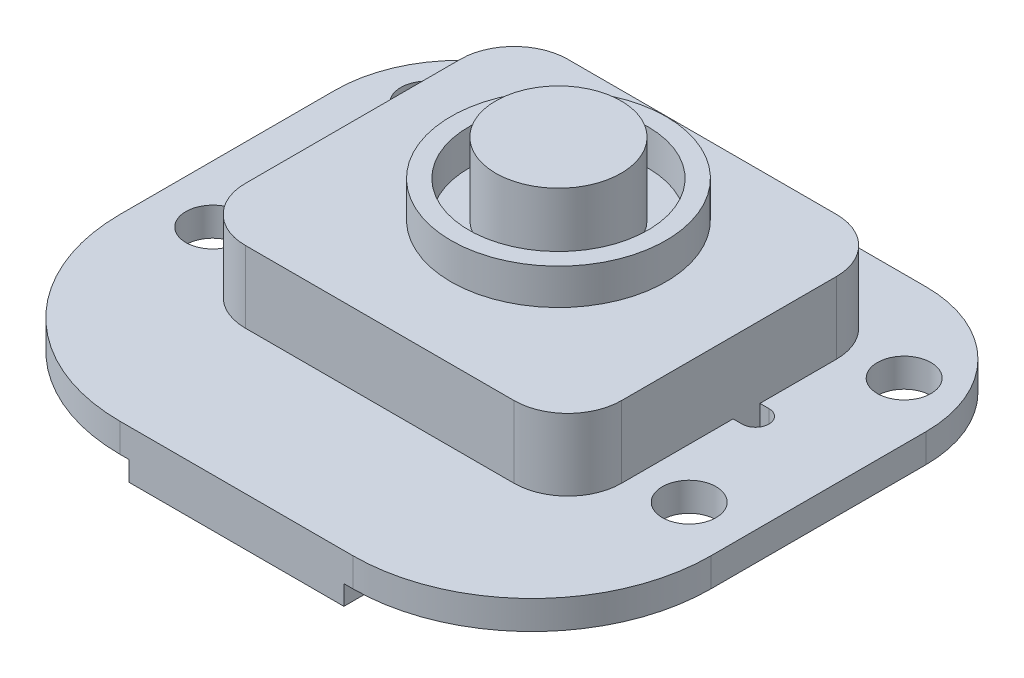
SolidWorks part; units mm, degrees
material "电源线路板"
ref_plane "前视基准面" through (0, 0, 0) normal (0, 0, 1) x (1, 0, 0)
ref_plane "上视基准面" through (0, 0, 0) normal (0, 1, 0) x (1, 0, 0)
ref_plane "右视基准面" through (0, 0, 0) normal (1, 0, 0) x (0, 0, -1)
other "Configuration Table"
sketch "草图1" plane through (0, 0, 0) normal (0, 1, 0) x (1, 0, 0)
  line L0 (0, 0) -> (0, -4.2094)
  line L1 (0, 0) -> (3.6442, 0)
  line L2 (-11, 0) -> (-10, 0) construction
  line L3 (-11, 0.75) -> (-10, 0.75)
  line L4 (-11, -0.75) -> (-10, -0.75)
  line L5 (11, 0) -> (10, 0) construction
  line L6 (11, 0.75) -> (10, 0.75)
  line L7 (-9.5, 11.0225) -> (9.5, 11.0225)
  line L8 (-16.5, 4.0225) -> (-16.5, -7.9775)
  line L9 (-6.5, -17.9775) -> (6.5, -17.9775)
  line L10 (16.5, 4.0225) -> (16.5, -7.9775)
  line L11 (11, -0.75) -> (10, -0.75)
  arc A0 (-16.5, 4.0225) -> (-9.5, 11.0225) centre (-9.5, 4.0225) cw
  arc A1 (16.5, 4.0225) -> (9.5, 11.0225) centre (9.5, 4.0225) ccw
  arc A2 (-6.5, -17.9775) -> (-16.5, -7.9775) centre (-6.5, -7.9775) cw
  arc A3 (16.5, -7.9775) -> (6.5, -17.9775) centre (6.5, -7.9775) cw
  circle A4 centre (-13.3, 6) radius 1.5
  circle A5 centre (13.3, 6) radius 1.5
  circle A6 centre (-13.3, -6) radius 1.5
  circle A7 centre (13.3, -6) radius 1.5
  arc A8 (-11, 0.75) -> (-11, -0.75) centre (-11, 0) ccw
  arc A9 (-10, -0.75) -> (-10, 0.75) centre (-10, 0) ccw
  arc A10 (11, 0.75) -> (11, -0.75) centre (11, 0) cw
  arc A11 (10, -0.75) -> (10, 0.75) centre (10, 0) cw
  point P27 (-10.5, 0)
  point P34 (10.5, 0)
  dimension "D12" = 7
  dimension "D13" = 7
  dimension "D14" = 10
  dimension "D15" = 10
  dimension "D2" = 13.3
  dimension "D10" = 1
  dimension "D3" = 13.3
  dimension "D4" = 12
  dimension "D5" = 6
  dimension "D6" = 6
  dimension "D7" = 12
  dimension "D8" = 0
  dimension "D9" = 0
  dimension "D11" = 10.5
extrude "凸台-拉伸1" add sketch "草图1" along normal blind 1.6
sketch "草图2" plane through (0, 0, 0) normal (0, 1, 0) x (1, 0, 0)
  line L0 (0, 0) -> (0, -3.1954)
  line L1 (-7.5, 8.0225) -> (7.5, 8.0225)
  line L2 (-10.5, 5.0225) -> (-10.5, -6.9775)
  line L3 (-7.5, -9.9775) -> (7.5, -9.9775)
  line L4 (10.5, 5.0225) -> (10.5, -6.9775)
  line L5 (-9.5, 11.0225) -> (9.5, 11.0225) construction
  line L6 (-6.5, -17.9775) -> (6.5, -17.9775) construction
  arc A0 (-10.5, 5.0225) -> (-7.5, 8.0225) centre (-7.5, 5.0225) cw
  arc A1 (10.5, 5.0225) -> (7.5, 8.0225) centre (7.5, 5.0225) ccw
  arc A2 (7.5, -9.9775) -> (10.5, -6.9775) centre (7.5, -6.9775) ccw
  arc A3 (-7.5, -9.9775) -> (-10.5, -6.9775) centre (-7.5, -6.9775) cw
  dimension "D5" = 3
  dimension "D6" = 3
  dimension "D7" = 3
  dimension "D8" = 3
  dimension "D1" = 10.5
  dimension "D2" = 10.5
  dimension "D3" = 3
  dimension "D4" = 8
extrude "凸台-拉伸2" add sketch "草图2" along normal blind 5.6
sketch "草图3" plane through (0, 0, 0) normal (0, 1, 0) x (1, 0, 0)
  circle A0 centre (0, 0) radius 6
  circle A1 centre (0, 0) radius 5
extrude "凸台-拉伸3" add sketch "草图3" along normal blind 7.6
sketch "草图4" plane through (0, 0, 0) normal (0, 1, 0) x (1, 0, 0)
  circle A0 centre (0, 0) radius 2.75
  circle A1 centre (0, 0) radius 3.5
  dimension "D1" = 5.5
extrude "凸台-拉伸4" add sketch "草图4" along normal blind 9.6
sketch "草图5" plane through (0, 0, 0) normal (0, 1, 0) x (1, 0, 0)
  circle A0 centre (0, 0) radius 3.5
extrude "凸台-拉伸5" add sketch "草图5" along normal blind 9.6
sketch "草图7" plane through (0, 0, 0) normal (0, 1, 0) x (1, 0, 0)
  line L0 (-6.5, -17.9775) -> (6.5, -17.9775) construction
  line L1 (6, -13.2607) -> (-6, -13.2607)
  line L2 (6, -13.2607) -> (6, -17.9775)
  line L3 (6, -17.9775) -> (-6, -17.9775)
  line L4 (-6, -13.2607) -> (-6, -17.9775)
  line L5 (0, 0) -> (0, -3.2289)
  dimension "D1" = 6
  dimension "D2" = 6
extrude "凸台-拉伸6" add sketch "草图7" along normal blind 0.001 and the other way blind 1.1 contours L1 L4 L3 L2
